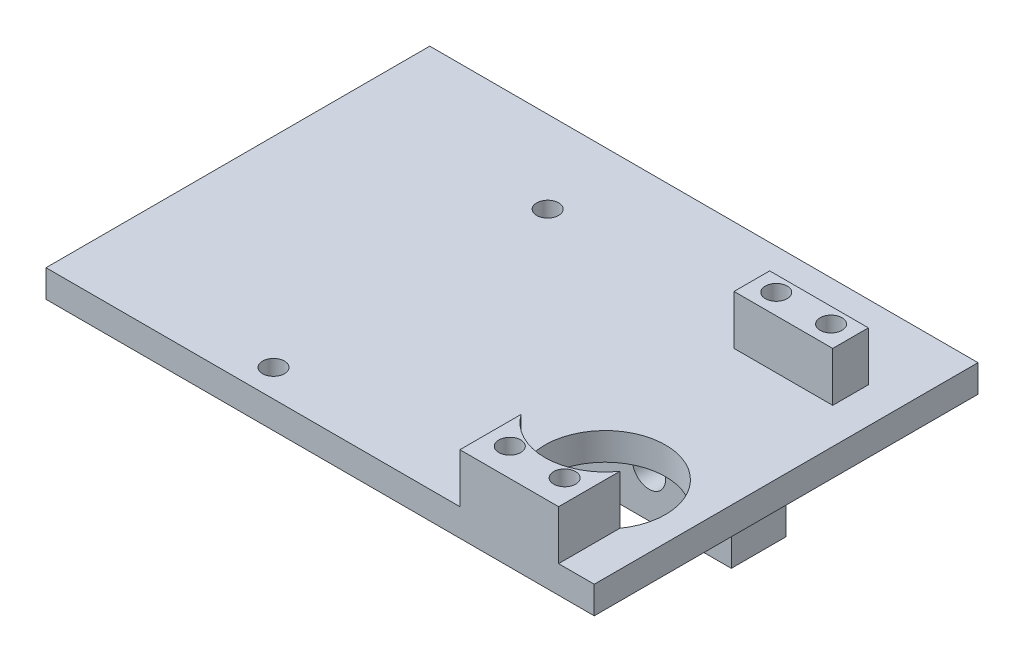
SolidWorks part; units mm, degrees
ref_plane "Front Plane" through (0, 0, 0) normal (0, 0, 1) x (1, 0, 0)
ref_plane "Top Plane" through (0, 0, 0) normal (0, 1, 0) x (1, 0, 0)
ref_plane "Right Plane" through (0, 0, 0) normal (1, 0, 0) x (0, 0, -1)
sketch "Sketch1" plane through (0, 0, 0) normal (0, 1, 0) x (1, 0, 0)
  line L1 (50, 35) -> (-50, 35)
  line L2 (50, 35) -> (50, -35)
  line L3 (50, -35) -> (-50, -35)
  line L4 (-50, 35) -> (-50, -35)
  line L5 (50, 35) -> (-50, -35) construction
  line L6 (50, -35) -> (-50, 35) construction
  circle A0 centre (34.5, -17.5) radius 11
  point P0 (0, 0)
  dimension "D4" = 15.5
  dimension "D5" = 22
  dimension "D1" = 100
  dimension "D2" = 70
  dimension "D3" = 17.5
extrude "Boss-Extrude1" add sketch "Sketch1" along normal blind 5
sketch "Sketch2" plane through (0, 5, 0) normal (0, 1, 0) x (1, 0, 0)
  line L0 (25.5, -35) -> (25.5, -23.8246)
  line L1 (-50, -35) -> (50, -35) construction
  line L2 (25.5, -23.8246) -> (43.5, -23.8246) construction
  line L3 (43.5, -23.8246) -> (43.5, -35)
  line L4 (50, -35) -> (50, 35) construction
  line L5 (50, 35) -> (-50, 35) construction
  line L6 (25.5, 21.5) -> (43.5, 21.5)
  line L7 (25.5, 21.5) -> (25.5, 15)
  line L8 (25.5, 15) -> (43.5, 15)
  line L9 (43.5, 21.5) -> (43.5, 15)
  line L10 (25.5, -35) -> (43.5, -35)
  arc A4 (25.5, -23.8246) -> (43.5, -23.8246) centre (34.5, -17.5) ccw
  circle A5 centre (34.5, -17.5) radius 11 construction
  point P9 (34.5, -23.8246)
  dimension "D2" = 22
  dimension "D1" = 6.5
  dimension "D3" = 20
  dimension "D4" = 13.5
extrude "Boss-Extrude2" add sketch "Sketch2" along normal blind 9
sketch "Sketch3" plane through (0, 14, 0) normal (0, 1, 0) x (1, 0, 0)
  line L0 (39.5, -35) -> (39.5, -29.9) construction
  line L1 (25.5, -35) -> (43.5, -35) construction
  line L2 (39.5, -29.9) -> (39.5, 18.7) construction
  line L3 (39.5, -29.9) -> (50, -29.9) construction
  line L4 (50, -35) -> (50, 35) construction
  line L5 (39.5, -29.9) -> (29.5, -29.9) construction
  line L6 (39.5, 18.7) -> (29.5, 18.7) construction
  circle A0 centre (29.5, -29.9) radius 2
  circle A1 centre (39.5, -29.9) radius 2
  circle A2 centre (39.5, 18.7) radius 2
  circle A3 centre (29.5, 18.7) radius 2
  point P14 (0, 0)
  dimension "D5" = 4
  dimension "D1" = 10
  dimension "D2" = 5.1
  dimension "D3" = 48.6
  dimension "D4" = 10.5
extrude "Cut-Extrude1" cut sketch "Sketch3" against normal blind 3
sketch "Sketch4" plane through (0, 0, -35) normal (0, 0, -1) x (-1, 0, 0)
  line L0 (-50, 0) -> (50, 0) construction
  line L1 (15, -40) -> (-15, -40)
  line L2 (15, -40) -> (15, 0)
  line L3 (15, 0) -> (-15, 0)
  line L4 (-15, -40) -> (-15, 0)
  line L5 (15, -40) -> (-15, 0) construction
  line L6 (15, 0) -> (-15, -40) construction
  line L7 (-50, 0) -> (-15, -7)
  line L8 (50, 0) -> (15, -7)
  line L9 (50, 0) -> (15, 0)
  line L10 (-15, 0) -> (-50, 0)
  circle A0 centre (0, -8) radius 3
  circle A1 centre (0, -32) radius 3
  point P0 (0, -20)
  point P18 (0, 0)
  line M4 (-50, 0) -> (50, 0)
  dimension "D3" = 6
  dimension "D5" = 8
  dimension "D1" = 30
  dimension "D2" = 40
  dimension "D4" = 8
  dimension "D6" = 7
extrude "Boss-Extrude4" add sketch "Sketch4" against normal blind 10 contours L4 L1 L2 A1 A0 M4 | L7 L4 M4 | L8 L2 M4
fillet "Fillet2" radius 3 3 edges at (0, 0, -25) (-15, -7, -30) (15, -7, -30)
sketch "Sketch5" plane through (0, 5, 0) normal (0, 1, 0) x (1, 0, 0)
  line L0 (-50, -35) -> (25.5, -35) construction
  line L1 (-50, 35) -> (-50, -35) construction
  circle A0 centre (-13.5, -30) radius 2
  circle A1 centre (-13.5, 20) radius 2
  dimension "D1" = 5
  dimension "D2" = 36.5
  dimension "D3" = 4
  dimension "D4" = 50
extrude "Cut-Extrude2" cut sketch "Sketch5" against normal up to surface (5 mm away) up to face at (0, 0, 6.5)
